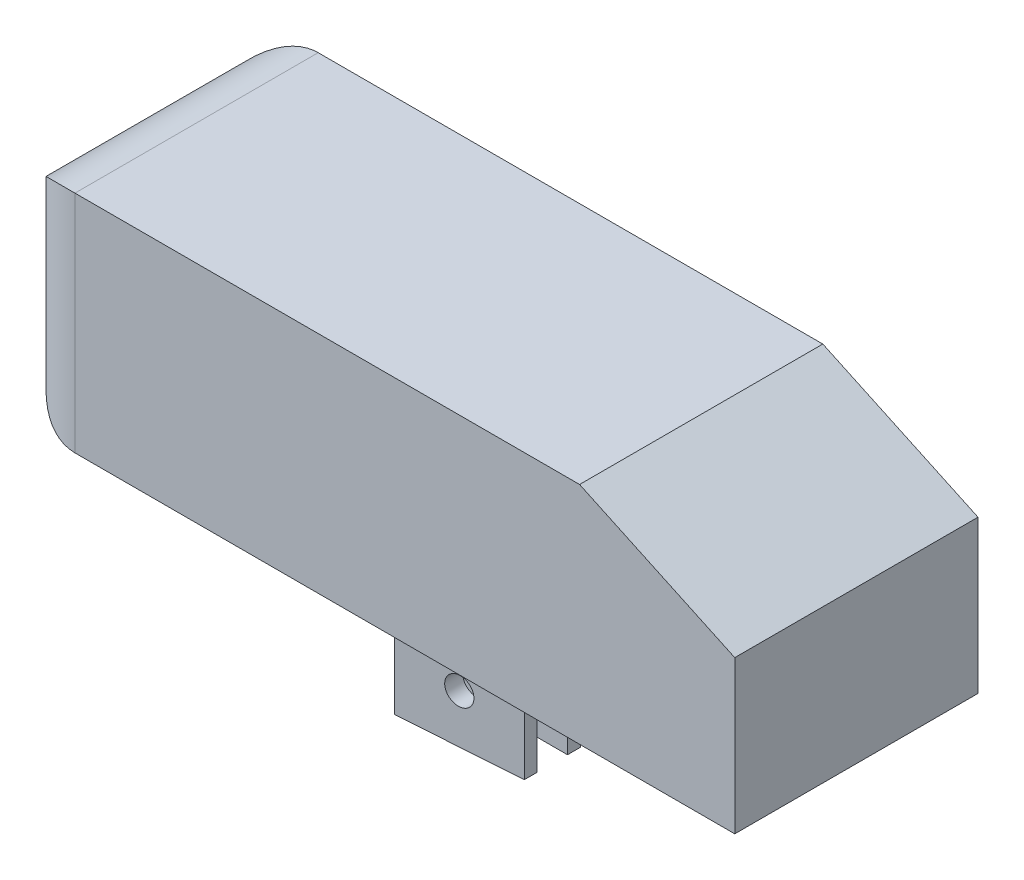
SolidWorks part; units mm, degrees
ref_plane "Front Plane" through (0, 0, 0) normal (0, 0, 1) x (1, 0, 0)
ref_plane "Top Plane" through (0, 0, 0) normal (0, 1, 0) x (1, 0, 0)
ref_plane "Right Plane" through (0, 0, 0) normal (1, 0, 0) x (0, 0, -1)
sketch "Sketch1" plane through (0, 0, 0) normal (0, 1, 0) x (1, 0, 0)
  line L1 (-522, 174) -> (522, 174)
  line L2 (-522, 174) -> (-522, -174)
  line L3 (-522, -174) -> (522, -174)
  line L4 (522, 174) -> (522, -174)
  line L5 (-522, 174) -> (522, -174) construction
  line L6 (-522, -174) -> (522, 174) construction
  point P0 (0, 0)
  dimension "D1" = 1044
  dimension "D2" = 348
extrude "Boss-Extrude1" add sketch "Sketch1" along normal blind 321.9 contours L1 L4 L3 L2
chamfer "Chamfer2" distance 222 angle 25 1 edges at (522, 321.9, 0)
fillet "Fillet1" radius 100 4 edges at (-522, 0, 0) (-522, 160.95, -174) (-522, 321.9, 0) (-522, 160.95, 174)
scale "Scale1" scale about centroid uniform scaling yes scale factor 0.115
ref_plane "Plane8" through (0, 174.4082, 0) normal (0, 1, 0) x (1, 0, 0)
sketch "Sketch175" plane through (0, 138.3897, 0) normal (0, -1, 0) x (1, 0, 0)
  line L0 (-64.4353, 0) -> (55.6247, 0) construction
  line L1 (-64.4353, -8.51) -> (-64.4353, 8.51) construction
  line L2 (55.6247, -20.01) -> (55.6247, 20.01) construction
  line L8 (5.5947, -6) -> (-14.4053, -6)
  line L9 (5.5947, -6) -> (5.5947, 6)
  line L10 (5.5947, 6) -> (-14.4053, 6)
  line L11 (-14.4053, -6) -> (-14.4053, 6)
  line L12 (5.5947, -6) -> (-14.4053, 6) construction
  line L13 (5.5947, 6) -> (-14.4053, -6) construction
  point P6 (-4.4053, 0)
  point P7 (-4.4053, 0)
  dimension "D1" = 12
  dimension "D2" = 20
extrude "Boss-Extrude12" add sketch "Sketch175" along normal blind 25
sketch "Sketch176" plane through (5.5947, 0, 0) normal (1, 0, 0) x (0, 0, -1)
  line L0 (6, 113.3897) -> (-6, 113.3897) construction
  line L1 (2.5, 113.3897) -> (-2.5, 113.3897)
  line L2 (2.5, 113.3897) -> (2.5, 138.3897)
  line L3 (2.5, 138.3897) -> (-2.5, 138.3897)
  line L4 (-2.5, 113.3897) -> (-2.5, 138.3897)
  line L5 (6, 138.3897) -> (-6, 138.3897) construction
  point P8 (0, 113.3897)
  point P9 (0, 113.3897)
  dimension "D1" = 5
extrude "Cut-Extrude1" cut sketch "Sketch176" against normal blind 30
sketch "Sketch177" plane through (0, 0, -6) normal (0, 0, -1) x (-1, 0, 0)
  line L0 (14.4053, 113.3897) -> (-5.5947, 113.3897) construction
  circle A0 centre (4.4053, 121.3897) radius 2.25
  point P4 (4.4053, 113.3897)
  dimension "D1" = 4.5
  dimension "D2" = 8
extrude "Cut-Extrude2" cut sketch "Sketch177" against normal blind 30
sketch "Sketch179" plane through (0, 113.3897, 0) normal (0, -1, 0) x (1, 0, 0)
  line L0 (-14.4053, 6) -> (20.5947, 3.5526)
  line L1 (20.5947, 3.5526) -> (20.5947, -3.5526)
  line L2 (20.5947, -3.5526) -> (-14.4053, -6)
  line L3 (5.5947, 6) -> (-14.4053, 6) construction
  line L4 (-14.4053, -6) -> (5.5947, -6) construction
  line L5 (-14.4053, 6) -> (23.5947, 6)
  line L6 (23.5947, 6) -> (23.5947, -6)
  line L7 (23.5947, -6) -> (-14.4053, -6)
  dimension "D1" = 35
  dimension "D2" = 4
  dimension "D3" = 4
  dimension "D4" = 3
extrude "Cut-Extrude4" cut sketch "Sketch179" against normal up to surface (25 mm away) up to face at (-4.4053, 138.3897, 4.25)
